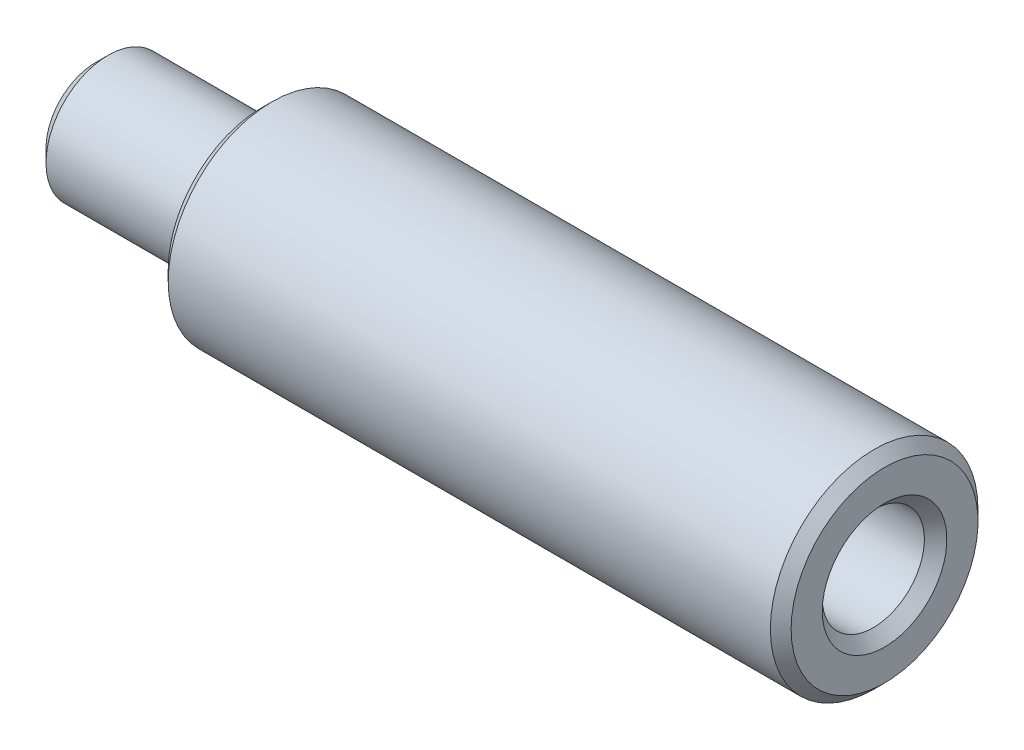
SolidWorks part; units mm, degrees
material "AISI 304"
ref_plane "Front Plane" through (0, 0, 0) normal (0, 0, 1) x (1, 0, 0)
ref_plane "Top Plane" through (0, 0, 0) normal (0, 1, 0) x (1, 0, 0)
ref_plane "Right Plane" through (0, 0, 0) normal (1, 0, 0) x (0, 0, -1)
ref_plane "Plane1" through (0, 0, 0) normal (0, 0, 1) x (1, 0, 0)
sketch "Sketch1" plane through (0, 0, 0) normal (0, 0, 1) x (1, 0, 0)
  line L0 (0, 0) -> (0, 4.5)
  line L1 (0, 4.5) -> (0.5, 5)
  line L2 (0.5, 5) -> (29.5, 5)
  line L3 (29.5, 5) -> (30, 4.5)
  line L4 (30, 4.5) -> (30, 0)
  line L5 (30, 0) -> (0, 0)
  line L6 (30, 0) -> (0, 0) construction
revolve "Revolve1" add sketch "Sketch1" angle 360 about L6
ref_plane "Plane2" through (0, 0, 0) normal (0, 0, 1) x (1, 0, 0)
sketch "Sketch2" plane through (0, 0, 0) normal (0, 0, 1) x (1, 0, 0)
  line L0 (-8, 0) -> (-8, 2.3865)
  line L1 (-8, 2.3865) -> (-7.3865, 3)
  line L2 (-7.3865, 3) -> (-0.5, 3)
  line L3 (0, 3.5) -> (0, 0)
  line L4 (0, 0) -> (-8, 0)
  line L5 (0, 0) -> (-8, 0) construction
  arc A0 (-0.5, 3) -> (0, 3.5) centre (-0.5, 3.5) ccw
revolve "Revolve2" add sketch "Sketch2" angle 360 about L5
cosmetic thread "Cosmetic Thread1" parameters "D1"=6, "D2"=4.773
ref_plane "Plane3" through (0, 0, 0) normal (0, 0, 1) x (1, 0, 0)
sketch "Sketch3" plane through (0, 0, 0) normal (0, 0, 1) x (1, 0, 0)
  line L0 (5, 0) -> (6.4194, 2.4585)
  line L1 (6.4194, 2.4585) -> (29.4585, 2.4585)
  line L2 (29.4585, 2.4585) -> (30, 3)
  line L3 (30, 3) -> (30, 0)
  line L4 (30, 0) -> (5, 0)
  line L5 (30, 0) -> (5, 0) construction
revolve "Cut-Revolve1" cut sketch "Sketch3" angle 360 about L5
cosmetic thread "Cosmetic Thread2"
